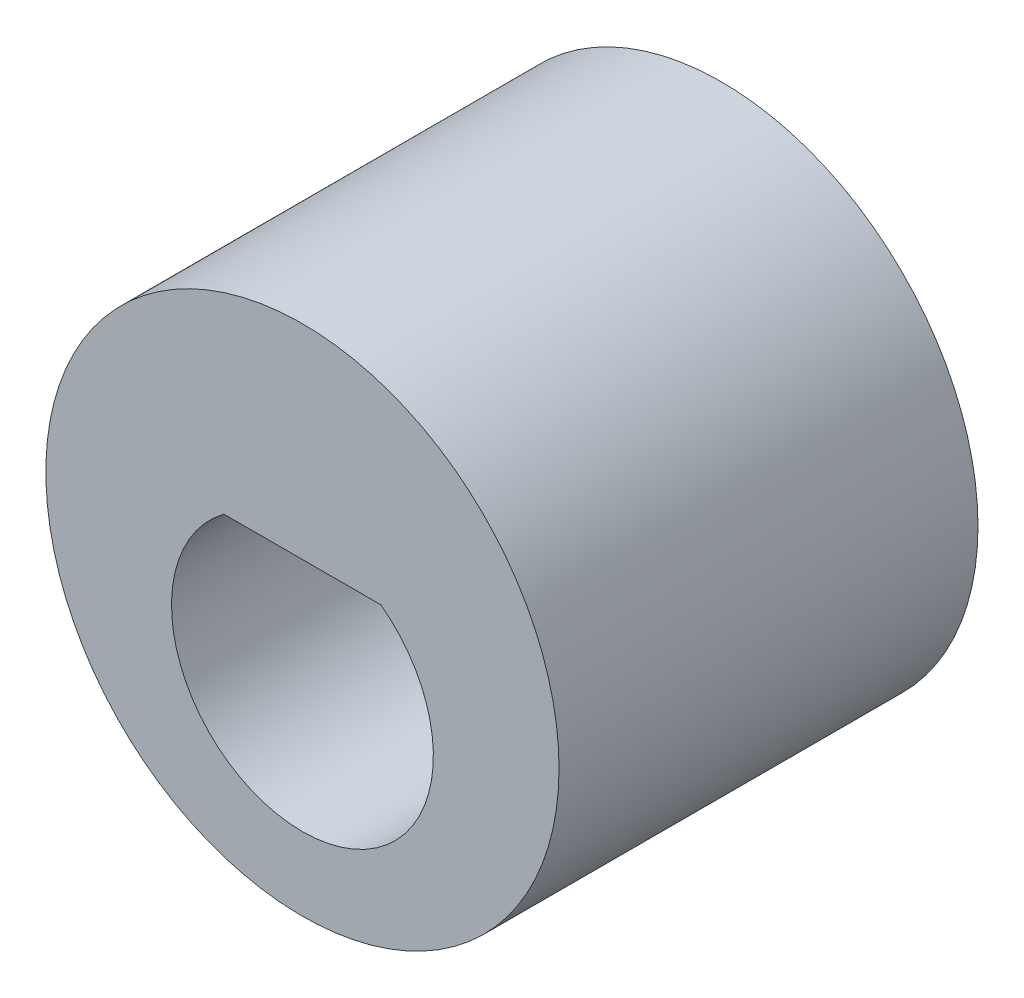
SolidWorks part; units mm, degrees
ref_plane "Plan de face" through (0, 0, 0) normal (0, 0, 1) x (1, 0, 0)
ref_plane "Plan de dessus" through (0, 0, 0) normal (0, 1, 0) x (1, 0, 0)
ref_plane "Plan de droite" through (0, 0, 0) normal (1, 0, 0) x (0, 0, -1)
sketch "Esquisse1" plane through (0, 0, 0) normal (0, 0, 1) x (1, 0, 0)
  line L0 (-1.5, 2) -> (1.5, 2)
  arc A0 (-1.5, 2) -> (1.5, 2) centre (0, 0) ccw
  circle A2 centre (0, 1) radius 4.9
  dimension "D1" = 2.5
  dimension "D2" = 2
  dimension "D4" = 9.8
  dimension "D5" = 1
extrude "Boss.-Extru.1" add sketch "Esquisse1" along normal blind 8
